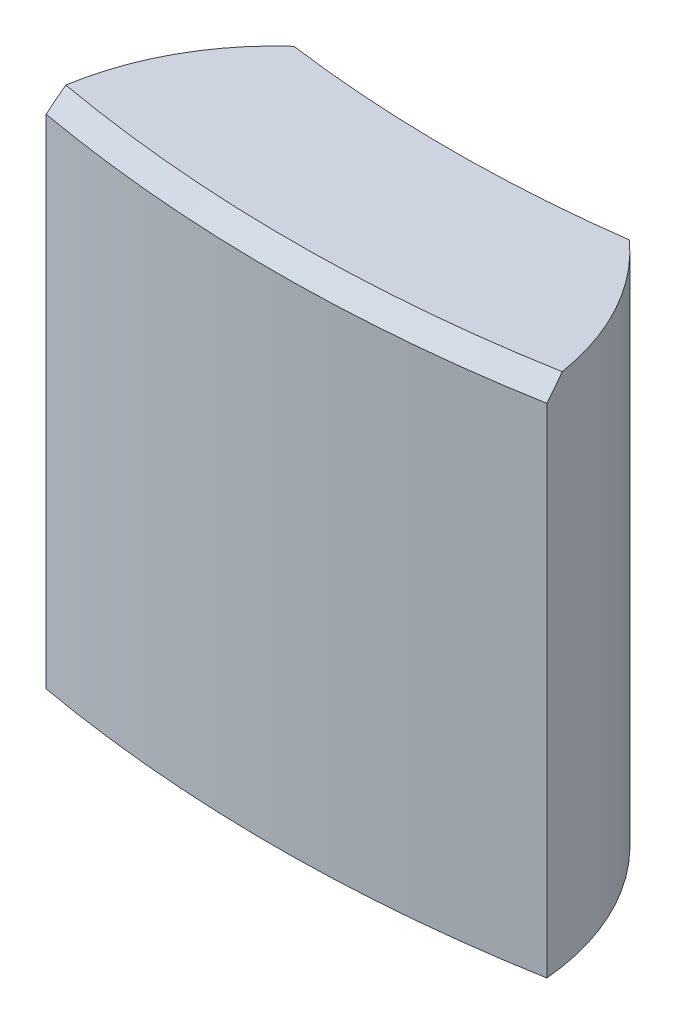
SolidWorks part; units mm, degrees
ref_plane "Front Plane" through (0, 0, 0) normal (0, 0, 1) x (1, 0, 0)
ref_plane "Top Plane" through (0, 0, 0) normal (0, 1, 0) x (1, 0, 0)
ref_plane "Right Plane" through (0, 0, 0) normal (1, 0, 0) x (0, 0, -1)
sketch "Sketch1" plane through (0, 0, 0) normal (0, 1, 0) x (1, 0, 0)
  arc A0 (-3.3368, -24.7763) -> (3.3368, -24.7763) centre (0, 0) ccw
  arc A1 (-4.9807, -28.0614) -> (4.9807, -28.0614) centre (0, 0) ccw
  arc A2 (-3.3368, -24.7763) -> (-4.9807, -28.0614) centre (0, -28.5) ccw
  arc A3 (4.9807, -28.0614) -> (3.3368, -24.7763) centre (0, -28.5) ccw
  dimension "D1" = 50
  dimension "D2" = 57
  dimension "D3" = 10
extrude "Boss-Extrude1" add sketch "Sketch1" along normal blind 10.9
chamfer "Chamfer1" distance 1 angle 45 1 edges at (0, 10.9, 28.5)
sketch "Sketch2" plane through (0, 10.9, 0) normal (0, 1, 0) x (1, 0, 0)
  circle A0 centre (0, 0) radius 39.7165
extrude "Cut-Extrude1" cut sketch "Sketch2" against normal blind 0.65
